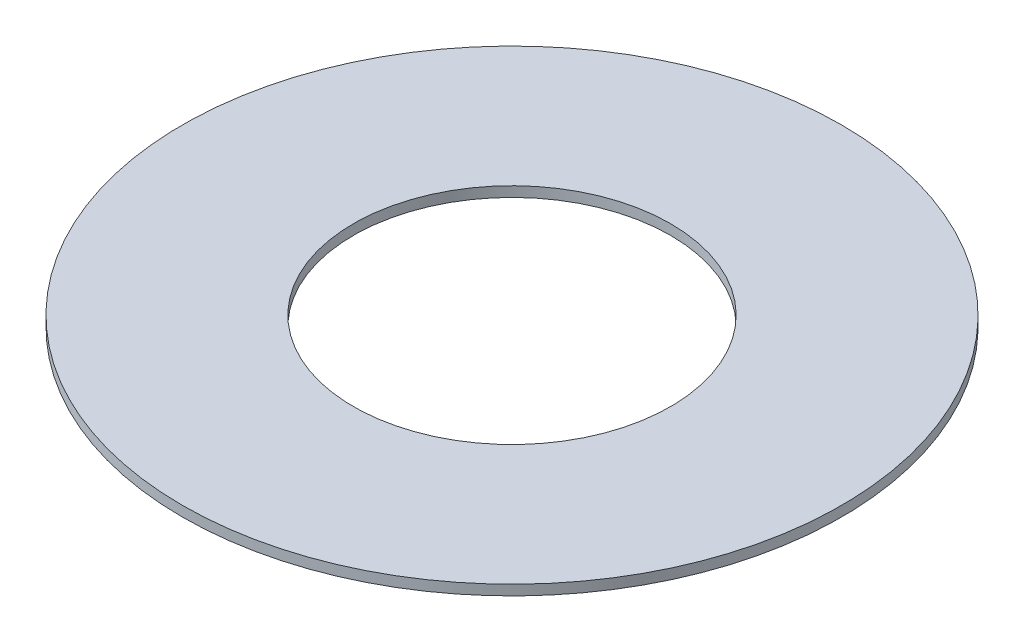
SolidWorks part; units mm, degrees
ref_plane "Front Plane" through (0, 0, 0) normal (0, 0, 1) x (1, 0, 0)
ref_plane "Top Plane" through (0, 0, 0) normal (0, 1, 0) x (1, 0, 0)
ref_plane "Right Plane" through (0, 0, 0) normal (1, 0, 0) x (0, 0, -1)
sketch "Sketch1" plane through (0, 0, 0) normal (0, 0, 1) x (1, 0, 0)
  line L0 (-327.5706, 9.4924) -> (-327.5706, 293.0344) construction
  line L1 (-111.2313, 23.3659) -> (122.184, 23.3659)
  line L2 (-111.2313, 23.3659) -> (-111.2313, 9.4924)
  line L3 (-111.2313, 9.4924) -> (122.184, 9.4924)
  line L4 (122.184, 23.3659) -> (122.184, 9.4924)
revolve "Revolve1" add sketch "Sketch1" angle 360 about L0
scale "Scale1" scale about centroid uniform scaling yes scale factor 5
scale "Scale2" scale about centroid uniform scaling yes scale factor 0.8
ref_plane "Plane1" through (0, -13.8578, 0) normal (0, 1, 0) x (1, 0, 0)
sketch "Sketch2" [suppressed] plane through (0, -13.8578, 0) normal (0, 1, 0) x (1, 0, 0)
  line L0 (-1656.8647, 0) -> (3039.6235, 0) construction
  line L1 (3039.6235, 0) -> (-327.5706, 0) construction
  line L2 (-327.5706, 0) -> (-327.5706, 1991.1009) construction
  line L3 (-327.5706, 1991.1009) -> (-327.5706, -2040.2194) construction
sketch "Sketch5" plane through (0, 44.1761, 0) normal (0, 1, 0) x (1, 0, 0)
  circle A0 centre (-327.5706, 0) radius 1799.0186 construction
  point P0 (-1762.0062, 1085.7544)
